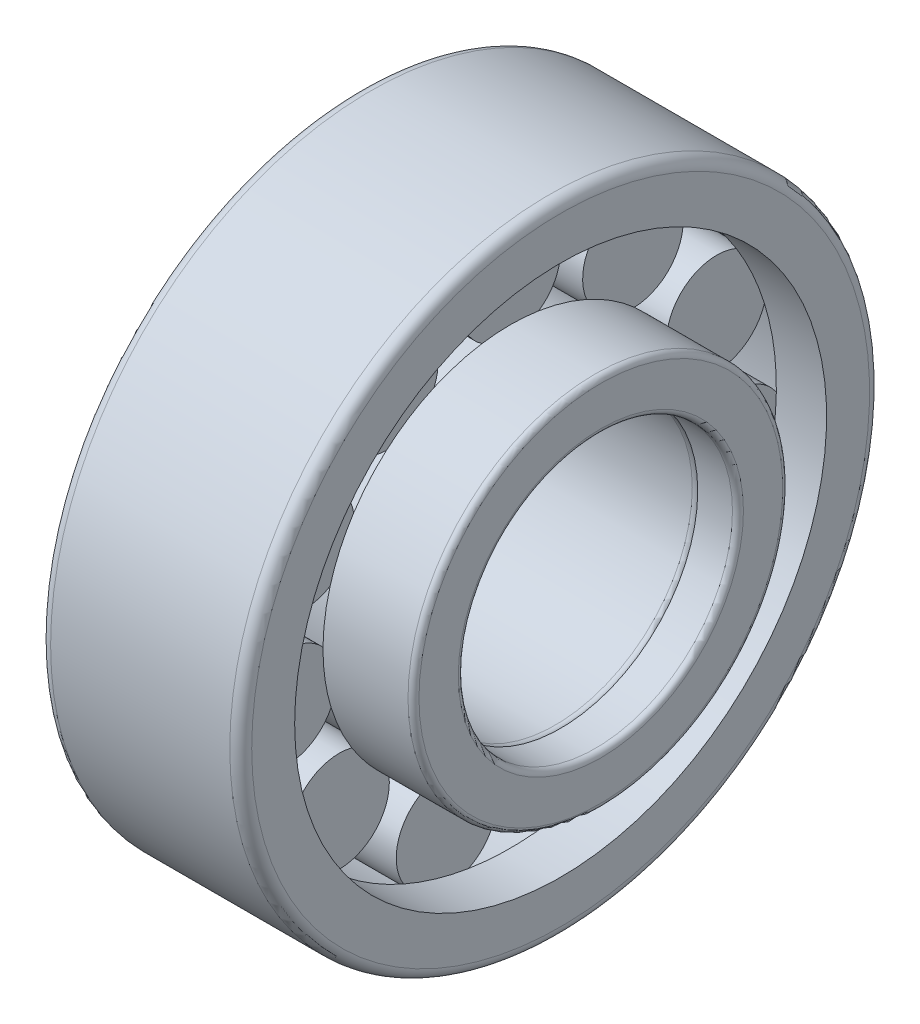
SolidWorks part; units mm, degrees
revolve "基体-旋转" add sketch "草图2" angle 360 about L0
sketch "草图2" plane through (0, 0, 0) normal (0, 0, 1) x (1, 0, 0)
  line L0 (-10.0801, 0) -> (21.9267, 0) construction
  line L1 (2.75, 9.65) -> (8.25, 9.65)
  line L2 (0, 10.25) -> (2.75, 10.25)
  line L3 (0, 10.25) -> (0, 7.8)
  line L4 (0.3, 7.5) -> (10.7, 7.5)
  line L5 (11, 8.9131) -> (11, 7.8)
  line L6 (2.75, 9.65) -> (2.75, 10.25)
  line L7 (11, 8.9131) -> (8.25, 9.65)
  arc A0 (10.7, 7.5) -> (11, 7.8) centre (10.7, 7.8) ccw
  arc A1 (0, 7.8) -> (0.3, 7.5) centre (0.3, 7.8) ccw
  point P13 (11, 7.5)
  point P16 (0, 7.5)
  dimension "D1" = 0.3
  dimension "DD" = 15
  dimension "D2" = 11
  dimension "FW" = 19.3
  dimension "D4" = 20.5
  dimension "D3" = 15
revolve "凸台-旋转1" add sketch "草图3" angle 360 about L2
sketch "草图3" plane through (0, 0, 0) normal (0, 0, 1) x (1, 0, 0)
  line L1 (8.25, 9.65) -> (8.25, -9.65) construction
  line L2 (-1.6039, 12.4) -> (13.5036, 12.4) construction
  line L4 (2.75, 12.4) -> (8.25, 12.4)
  line L5 (2.75, 12.4) -> (2.75, 9.6499)
  line L6 (2.75, 9.6499) -> (8.25, 9.6499)
  line L7 (8.25, 12.4) -> (8.25, 9.6499)
  line L8 (2.75, -10.25) -> (2.75, 10.25) construction
  dimension "D1" = 12.4
  dimension "D2" = 2.7501
revolve "凸台-旋转2" add sketch "草图4" angle 360 about L0
sketch "草图4" plane through (0, 0, 0) normal (0, 0, 1) x (1, 0, 0)
  line L0 (0, 0) -> (17.8006, 0) construction
  line L1 (-10.0801, 0) -> (21.9267, 0) construction
  line L2 (8.25, 14.55) -> (11, 14.55)
  line L3 (0.6, 17.5) -> (10.4, 17.5)
  line L4 (0, 16.9) -> (0, 14.55)
  line L5 (0, 14.55) -> (2.75, 14.55)
  line L6 (11, 16.9) -> (11, 14.55)
  line L7 (2.75, 15.15) -> (8.25, 15.15)
  line L8 (2.75, 15.15) -> (2.75, 14.55)
  line L10 (8.25, 15.15) -> (8.25, 14.55)
  arc A0 (10.4, 17.5) -> (11, 16.9) centre (10.4, 16.9) cw
  arc A1 (0.6, 17.5) -> (0, 16.9) centre (0.6, 16.9) ccw
  point P15 (11, 17.5)
  point P18 (0, 17.5)
  dimension "D2" = 0.6
  dimension "B" = 11
  dimension "EW" = 30.3
  dimension "D" = 35
  dimension "D3" = 0.6
material "GCr4"
ref_plane "基准面1" through (0, 0, 0) normal (0, 0, 1) x (1, 0, 0)
ref_plane "基准面2" through (0, 0, 0) normal (0, 1, 0) x (1, 0, 0)
ref_plane "基准面3" through (0, 0, 0) normal (1, 0, 0) x (0, 0, -1)
sketch "尺寸草图" plane through (0, 0, 0) normal (0, 0, 1) x (1, 0, 0)
  line L0 (0, 0) -> (0.3, 0)
  line L1 (0.3, 0) -> (0.9, 0)
  line L2 (0.9, 0) -> (11.9, 0)
  line L3 (11.9, 0) -> (26.9, 0)
  line L4 (26.9, 0) -> (46.2, 0)
  line L5 (46.2, 0) -> (81.2, 0)
  line L6 (111.5, 0) -> (113.7, 0)
  line L7 (81.2, 0) -> (111.5, 0)
  dimension "倒角小" = 0.3
  dimension "倒角大" = 0.6
  dimension "宽度" = 11
  dimension "内径" = 15
  dimension "参考FW" = 19.3
  dimension "外径" = 35
  dimension "参考EW" = 30.3
  dimension "架宽度" = 2.2
sketch "草图5" plane through (0, 0, 0) normal (0, 0, 1) x (1, 0, 0)
  line L0 (0, 0) -> (19.6659, 0) construction
  line L1 (-10.0801, 0) -> (21.9267, 0) construction
  line L2 (11, 8.9131) -> (11, 7.5)
  line L3 (11, -8.9131) -> (11, 8.9131) construction
  line L4 (11, -7.8) -> (11, 7.8) construction
  line L5 (11, 8.9131) -> (8.25, 9.65)
  line L6 (11, -14.55) -> (11, 14.55) construction
  line L7 (8.25, 9.65) -> (8.25, 10.25)
  line L8 (8.25, 10.25) -> (12.9, 10.25)
  line L9 (13.2, 9.95) -> (13.2, 7.8)
  line L10 (12.9, 7.5) -> (11, 7.5)
  arc A0 (12.9, 10.25) -> (13.2, 9.95) centre (12.9, 9.95) cw
  arc A1 (12.9, 7.5) -> (13.2, 7.8) centre (12.9, 7.8) ccw
  dimension "D1" = 0.3
  dimension "D4" = 20.5
  dimension "D2" = 15
  dimension "D3" = 105
  dimension "D5" = 2.2
revolve "凸台-旋转3" add sketch "草图5" angle 360 about L0
pattern_circular "阵列(圆周)1" count 11 over 360 about axis through (0, 0, 0) along (1, 0, 0) of "凸台-旋转1"
equation "\"DD@草图2\" = \"内径@尺寸草图\""
equation "\"FW@草图2\" = \"参考FW@尺寸草图\""
equation "\"D1@草图2\" = \"倒角小@尺寸草图\""
equation "\"EW@草图4\" = \"参考EW@尺寸草图\""
equation "\"B@草图4\" = \"宽度@尺寸草图\""
equation "\"D@草图4\" = \"外径@尺寸草图\""
equation "\"D2@草图4\" = \"倒角大@尺寸草图\""
equation "\"架宽度@尺寸草图\" = 0.20*\"宽度@尺寸草图\""
equation "\"D5@草图5\" = \"架宽度@尺寸草图\""
equation "\"D4@草图2\" = \"FW@草图2\" + 4 *\"D1@草图2\""
equation "\"D2@草图2\" = \"B@草图4\""
equation "\"滚珠位置@草图2\" = \"D2@草图2\"/4"
equation "\"D3@草图4\" = \"D2@草图4\""
equation "\"D1@草图3\" =  ( \"EW@草图4\" - \"FW@草图2\" )  / 4 + \"FW@草图2\" / 2"
equation "\"D2@草图3\" =  0.25*( \"EW@草图4\" - \"FW@草图2\" ) +0.0001"
equation "\"D1@阵列(圆周)1\" =0.75* \"D1@草图3\" * 3.14 / \"D2@草图3\""
equation "\"D1@草图5\" = \"D1@草图2\""
equation "\"D4@草图5\" = \"D4@草图2\""
equation "\"D2@草图5\" = \"DD@草图2\""
